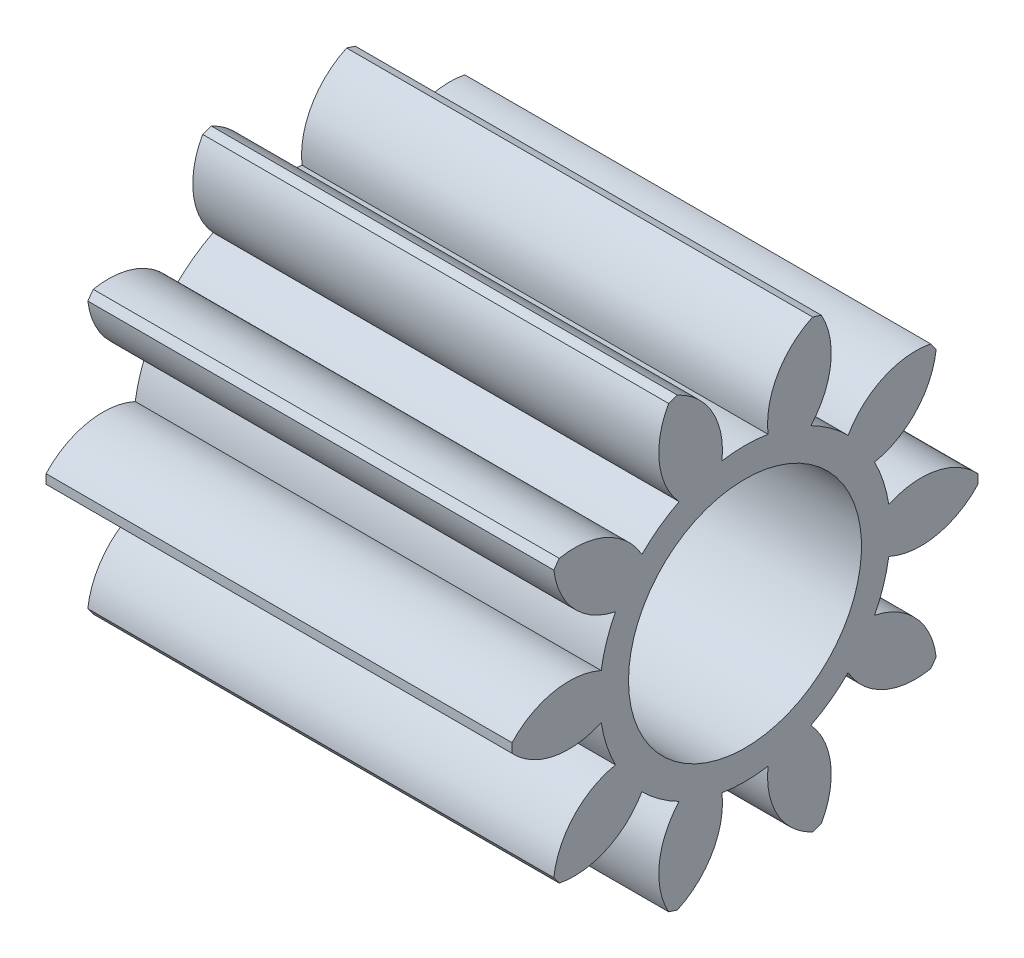
SolidWorks part; units mm, degrees
material "PVC 0.007 Plasticized"
ref_plane "Plane1" through (0, 0, 0) normal (0, 0, 1) x (1, 0, 0)
ref_plane "Plane2" through (0, 0, 0) normal (0, 1, 0) x (1, 0, 0)
ref_plane "Plane3" through (0, 0, 0) normal (1, 0, 0) x (0, 0, -1)
sketch "HoldingSke" plane through (0, 0, 0) normal (0, 1, 0) x (1, 0, 0)
  line L0 (0, 0) -> (1.9696, -0.3473)
  line L1 (-15, 0) -> (100, 0) construction
  line L2 (0, 0) -> (-2.1039, 2.3779)
  line L3 (0, 0) -> (-11.863, 4.5341)
  line L4 (0, 0) -> (8.5048, 1.4996)
  line L5 (0, 0) -> (-46.8476, -17.4728)
  line L6 (0, 0) -> (-4.9738, -3.3558)
  line L7 (-2.1039, 2.3779) -> (8.6586, 51.2059)
  line L8 (-76.2, 54.61) -> (-75.7, 54.61)
  line L9 (-71.009, 38.7566) -> (-53.1078, 45.2721)
  line L10 (-76.2, 71.12) -> (104.1128, 71.12)
  line L11 (0, 0) -> (-6, 0)
  line L12 (-76.2, 101.6) -> (-76.181, 101.6)
  line L13 (24.9733, 27.94) -> (52.9518, 28.4284)
  line L14 (24.9733, 27.94) -> (24.9743, 27.94)
  line L15 (24.9733, 27.94) -> (100.4006, 29.5858)
  line L16 (-63.627, -0.5) -> (-12.827, -0.5)
  circle A0 centre (0, 0) radius 1.5
  circle A1 centre (0, 0) radius 1.874
  circle A2 centre (0, 0) radius 37.5
  circle A3 centre (0, 0) radius 1.5
  dimension "MHD" = 3.748
  dimension "Hub_dia" = 75
  dimension "Bore" = 3
  dimension "MBD" = 3
  dimension "Num_teeth" = 10
  dimension "Pitch" = 2
  dimension "Overall_len" = 50
  dimension "Show_teeth" = 10
  dimension "Thickness" = 6
  dimension "OAL" = 50.0001
  dimension "T_dim" = 0.5
  dimension "Ap" = 20
  dimension "H" = 19.05
  dimension "Pitch_radius" = 180.3128
  dimension "Width" = 6
  dimension "Backlash" = 0.019
  dimension "Addendum_fac" = 1
  dimension "Dedendum_fac" = 1.25
  dimension "Clearance_fac" = 0.25
  dimension "Dedendum_add" = 0.001
  dimension "Module" = 0.5
sketch "BasProSke" plane through (0, 0, 0) normal (0, 1, 0) x (1, 0, 0)
  line L0 (-10, 0) -> (60, 0) construction
  line L1 (0, 0) -> (0, 3)
  line L2 (0, 0) -> (6, 0)
  line L3 (6, 0) -> (6, 3)
  line L4 (6, 3) -> (0, 3)
  dimension "Thickness" = 6
  dimension "Diameter" = 6
revolve "Base-Revolve" add sketch "BasProSke" angle 360 about L0
sketch "TooCutSke" plane through (0, 0, 0) normal (1, 0, 0) x (0, 0, -1)
  line L1 (0, 0) -> (0, 107) construction
  line L2 (0, 0) -> (-0.4243, 2.4637) construction
  line L3 (0, 0) -> (-1.5292, 4.7063) construction
  line L4 (-0.4243, 2.4637) -> (-0.7646, 2.3532) construction
  arc A0 (0.2964, 1.8504) -> (-0.2964, 1.8504) centre (0, 0) ccw
  arc A1 (0.9059, 2.8866) -> (-0.9059, 2.8866) centre (0, 0) ccw
  circle A2 centre (0, 0) radius 2.5 construction
  circle A3 centre (0, 0) radius 2.3492 construction
  arc A4 (-0.2964, 1.8504) -> (-0.9059, 2.8866) centre (-1.2901, 1.9633) ccw
  arc A5 (0.9059, 2.8866) -> (0.2964, 1.8504) centre (1.2901, 1.9633) ccw
  dimension "Root_dia" = 3.748
  dimension "Overcut_dia" = 6.0508
  dimension "Pitch_dia" = 5
  dimension "Base_dia" = 4.6985
  dimension "Flank_rad" = 1
  dimension "Half_ang" = 18
  dimension "Half_CT" = 0.3578
extrude "ToothCut" cut sketch "TooCutSke" along normal through all
fillet "Breaks" [suppressed] radius 0.01
fillet "RootFillets" [suppressed] radius 0.126
pattern_circular "TeethCuts" count 10 over 360 about axis through (0, 0, 0) along (1, 0, 0) of "ToothCut", "RootFillets", "Breaks"
sketch "HubNeaOneSke" plane through (0, 0, 0) normal (-1, 0, 0) x (0, 0, 1)
  circle A0 centre (0, 0) radius 1.874
  dimension "Diameter" = 3.748
extrude "HubNearOne" [suppressed] add sketch "HubNeaOneSke" along normal blind 44.0001
sketch "HubNeaBotSke" plane through (0, 0, 0) normal (-1, 0, 0) x (0, 0, 1)
  circle A0 centre (0, 0) radius 1.874
  dimension "Diameter" = 3.748
extrude "HubNearBoth" [suppressed] add sketch "HubNeaBotSke" along normal blind 22
ref_plane "FarPln" through (6, 0, 0) normal (1, 0, 0) x (0, 0, -1)
sketch "HubFarSke" plane through (6, 0, 0) normal (1, 0, 0) x (0, 0, -1)
  circle A0 centre (0, 0) radius 1.874
  dimension "Diameter" = 3.748
extrude "HubFar" [suppressed] add sketch "HubFarSke" along normal blind 22
sketch "BorSke" plane through (0, 0, 0) normal (1, 0, 0) x (0, 0, -1)
  circle A0 centre (0, 0) radius 1.5
extrude "Bore" cut sketch "BorSke" along normal mid plane 100.0001
sketch "KeySke" plane through (0, 0, 0) normal (1, 0, 0) x (0, 0, -1)
  line L0 (-0.6, 0) -> (-0.6, 2)
  line L1 (-0.6, 2) -> (0.6, 2)
  line L2 (0.6, 2) -> (0.6, 0)
  line L3 (0, 0) -> (0, 34) construction
  line L4 (-0.6, 0) -> (0.6, 0)
  dimension "Offset" = 2
  dimension "Width" = 1.2
extrude "Keyway" [suppressed] cut sketch "KeySke" along normal mid plane 100.0001
pattern_circular "Keyway2" [suppressed] count 2 every 90 about axis through (-10, 0, 0) along (1, 0, 0)
equation "' \"Module@HoldingSke\" = 6.35"
equation "' \"Num_teeth@HoldingSke\" = 12"
equation "' \"Ap@HoldingSke\" =  20"
equation "' \"Ap@HoldingSke\" = 20"
equation "' \"Width@HoldingSke\" = 0.5 * 25.4"
equation "' \"Hub_dia@HoldingSke\"= 1 * 25.4"
equation "' \"Hub_dia@HoldingSke\" = 1 * 25.4"
equation "' \"Overall_len@HoldingSke\" = 1.0 * 25.4"
equation "' \"Bore@HoldingSke\" = 0.75 * 25.4"
equation "' \"T_dim@HoldingSke\" = 0.1 * 25.4"
equation "' \"Width@KeySke\" = 0.25 * 25.4"
equation "' \"Show_teeth@HoldingSke\" = 13"
equation "' \"Backlash@HoldingSke\" = 0.009 * 25.4"
equation "' \"Addendum_fac@HoldingSke\" = 1.0"
equation "' \"Dedendum_fac@HoldingSke\" = 1.25"
equation "' \"Dedendum_add@HoldingSke\" = 0.00005 * 25.4"
equation "' \"Clearance_fac@HoldingSke\" = 0.25"
equation "\"Pitch@HoldingSke\" = 1 / \"Module@HoldingSke\""
equation "\"Overcut_dia@TooCutSke\" = (\"Num_teeth@HoldingSke\" + 2 * \"Addendum_fac@HoldingSke\") / \"Pitch@HoldingSke\" + 0.002 * 25.4"
equation "\"Pitch_dia@TooCutSke\" = \"Num_teeth@HoldingSke\" / \"Pitch@HoldingSke\""
equation "\"Base_dia@TooCutSke\" = \"Num_teeth@HoldingSke\" / \"Pitch@HoldingSke\" * cos((\"Ap@HoldingSke\"  * 3.14159265 / 180))"
equation "\"Root_dia@TooCutSke\" = (\"Num_teeth@HoldingSke\" + 2) / \"Pitch@HoldingSke\" - 2 * (\"Addendum_fac@HoldingSke\" + \"Dedendum_fac@HoldingSke\") / \"Pitch@HoldingSke\" - \"Dedendum_add@HoldingSke\" * 2"
equation "\"Half_ang@TooCutSke\" = 180 / \"Num_teeth@HoldingSke\""
equation "\"Half_CT@TooCutSke\" = \"Num_teeth@HoldingSke\" / \"Pitch@HoldingSke\" * sin((3.14159265 / 2 / \"Num_teeth@HoldingSke\")) / 2 - 7 * \"Backlash@HoldingSke\" / 4"
equation "\"Flank_rad@TooCutSke\" = \"Num_teeth@HoldingSke\" / \"Pitch@HoldingSke\" / 5"
equation "\"Radius@RootFillets\" = \"Clearance_fac@HoldingSke\" / \"Pitch@HoldingSke\" + \"Dedendum_add@HoldingSke\""
equation "\"Break_rad@Breaks\" = 0.02 / \"Pitch@HoldingSke\""
equation "\"Thickness@HoldingSke\" = \"Width@HoldingSke\""
equation "\"OAL@HoldingSke\" = \"Thickness@HoldingSke\""
equation "\"MHD@HoldingSke\" = (\"Num_teeth@HoldingSke\" + 2) / \"Pitch@HoldingSke\" - 2 * (\"Addendum_fac@HoldingSke\" + \"Dedendum_fac@HoldingSke\")  / \"Pitch@HoldingSke\" - \"Dedendum_add@HoldingSke\" * 2"
equation "\"MBD@HoldingSke\" = (\"Num_teeth@HoldingSke\" + 2) / \"Pitch@HoldingSke\" - 2 * (\"Addendum_fac@HoldingSke\" + \"Dedendum_fac@HoldingSke\")  / \"Pitch@HoldingSke\" - \"Dedendum_add@HoldingSke\" * 2 - 0.002 * 25.4"
equation "\"MHD@HoldingSke\" = ((sgn( \"MHD@HoldingSke\" - \"Hub_dia@HoldingSke\" )-1)*( \"MHD@HoldingSke\" - \"Hub_dia@HoldingSke\" ))/-2+ \"Hub_dia@HoldingSke\""
equation "\"MBD@HoldingSke\" = ((sgn( \"MBD@HoldingSke\" - \"Bore@HoldingSke\" )-1)*( \"MBD@HoldingSke\" - \"Bore@HoldingSke\" ))/-2+ \"Bore@HoldingSke\""
equation "\"OAL@HoldingSke\" = ((sgn( \"OAL@HoldingSke\" - \"Overall_len@HoldingSke\" )+1)*( \"OAL@HoldingSke\" - \"Overall_len@HoldingSke\" ))/2 + \"Overall_len@HoldingSke\" + 0.000002 * 25.4"
equation "\"Num_teeth@TeethCuts\" = int( \"Show_teeth@HoldingSke\" ) + 1"
equation "\"Num_teeth@TeethCuts\" = ((sgn( \"Num_teeth@TeethCuts\" - \"Num_teeth@HoldingSke\" )-1)*( \"Num_teeth@TeethCuts\" - \"Num_teeth@HoldingSke\" ))/-2+ \"Num_teeth@HoldingSke\""
equation "\"Num_teeth@TeethCuts\" = ((sgn( \"Num_teeth@TeethCuts\" - 2.0)+1)*( \"Num_teeth@TeethCuts\" - 2.0))/2 +2.0"
equation "\"Angle@TeethCuts\" = 360.0 / \"Num_teeth@HoldingSke\""
equation "\"Diameter@BasProSke\" = (\"Num_teeth@HoldingSke\" + 2 * \"Addendum_fac@HoldingSke\") / \"Pitch@HoldingSke\""
equation "\"Thickness@BasProSke\"  = \"Thickness@HoldingSke\""
equation "' \"Fillet_rad@BasProSke\" =  \"Thickness@HoldingSke\" * 0.05"
equation "' \"Fillet_rad@BasProSke\" = \"Thickness@HoldingSke\" * 0.05"
equation "\"MHD@HoldingSke\" = ((sgn( \"MHD@HoldingSke\" - \"Root_dia@TooCutSke\" )-1)*( \"MHD@HoldingSke\" - \"Root_dia@TooCutSke\" ))/-2+ \"Root_dia@TooCutSke\""
equation "\"Diameter@HubNeaOneSke\" = \"MHD@HoldingSke\""
equation "\"Length@HubNearOne\" = \"OAL@HoldingSke\" - \"Thickness@BasProSke\""
equation "\"Diameter@HubNeaBotSke\" = \"MHD@HoldingSke\""
equation "\"Length@HubNearBoth\" = ( \"OAL@HoldingSke\" - \"Thickness@BasProSke\" ) / 2.0"
equation "\"Thickness@FarPln\" = \"Thickness@BasProSke\""
equation "\"Diameter@HubFarSke\" = \"MHD@HoldingSke\""
equation "\"Length@HubFar\" = ( \"OAL@HoldingSke\" - \"Thickness@BasProSke\" ) / 2.0"
equation "\"Diameter@BorSke\" = \"MBD@HoldingSke\""
equation "\"D1@Bore\" = \"OAL@HoldingSke\" * 2.0"
equation "\"D1@Keyway\" = \"OAL@HoldingSke\" * 2.0"
equation "\"Offset@KeySke\" = \"T_dim@HoldingSke\" + \"MBD@HoldingSke\" / 2.0"
